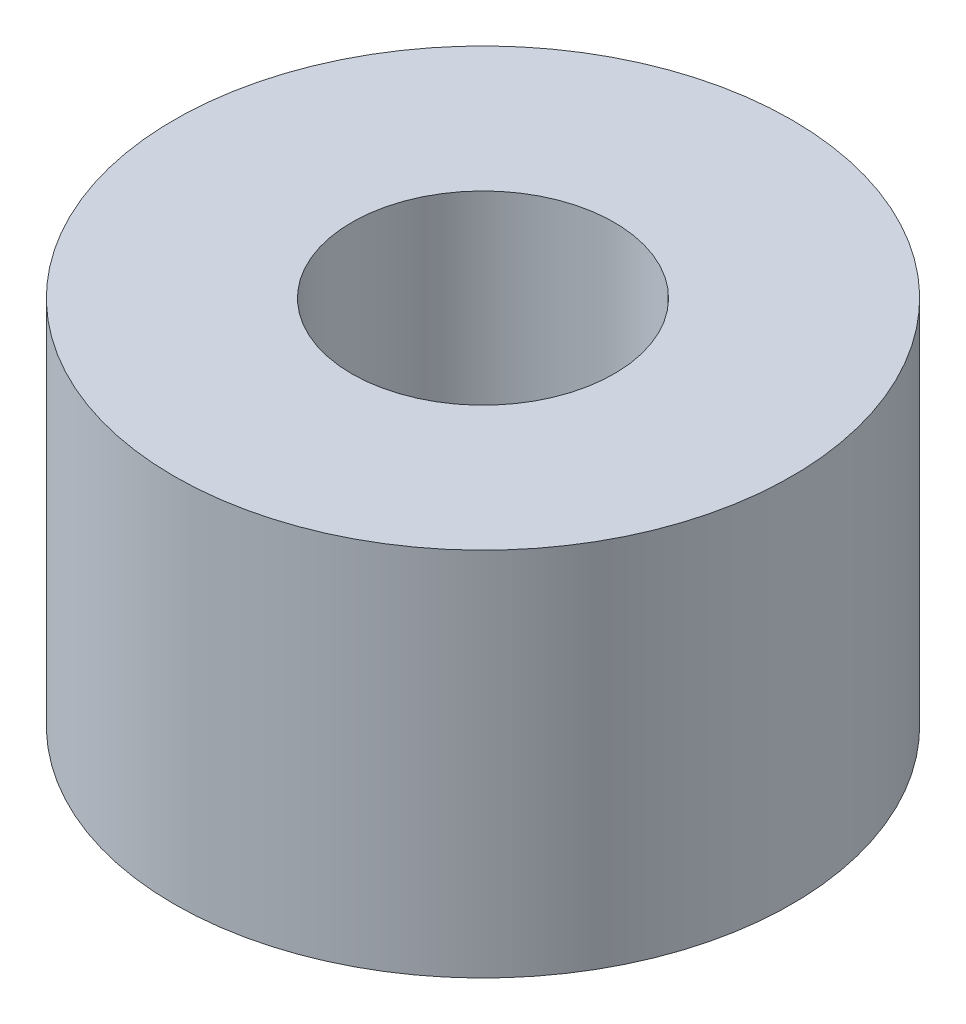
SolidWorks part; units mm, degrees
ref_plane "Alzado" through (0, 0, 0) normal (0, 0, 1) x (1, 0, 0)
ref_plane "Planta" through (0, 0, 0) normal (0, 1, 0) x (1, 0, 0)
ref_plane "Vista lateral" through (0, 0, 0) normal (1, 0, 0) x (0, 0, -1)
sketch "Croquis1" plane through (0, 0, 0) normal (0, 1, 0) x (1, 0, 0)
  circle A0 centre (0, 0) radius 5
  circle A1 centre (0, 0) radius 2.125
  dimension "D1" = 10
  dimension "D2" = 4.25
extrude "Saliente-Extruir1" add sketch "Croquis1" along normal blind 6
